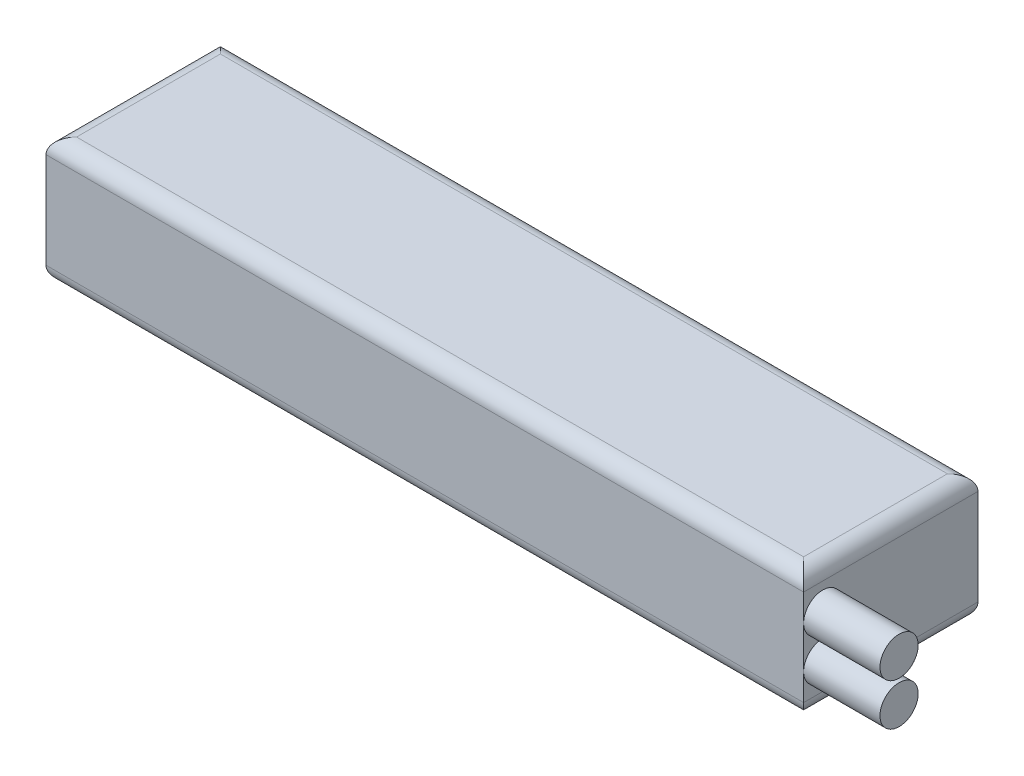
SolidWorks part; units mm, degrees
ref_plane "Front Plane" through (0, 0, 0) normal (0, 0, 1) x (1, 0, 0)
ref_plane "Top Plane" through (0, 0, 0) normal (0, 1, 0) x (1, 0, 0)
ref_plane "Right Plane" through (0, 0, 0) normal (1, 0, 0) x (0, 0, -1)
sketch "Sketch1" plane through (0, 0, 0) normal (0, 1, 0) x (1, 0, 0)
  line L1 (-2.7063, 0.7738) -> (123.2937, 0.7738)
  line L2 (-2.7063, 0.7738) -> (-2.7063, -28.2262)
  line L3 (-2.7063, -28.2262) -> (123.2937, -28.2262)
  line L4 (123.2937, 0.7738) -> (123.2937, -28.2262)
  dimension "D1" = 29
  dimension "D2" = 126
extrude "Boss-Extrude1" add sketch "Sketch1" along normal blind 21
sketch "Sketch2" plane through (123.2937, 0, 0) normal (1, 0, 0) x (0, 0, -1)
  line L0 (-28.2262, 10.5) -> (8.6283, 10.5) construction
  line L1 (-28.2262, 21) -> (-28.2262, 0) construction
  line L3 (-28.2262, 17.1675) -> (-21.8762, 17.1675) construction
  line L4 (-28.2262, 17.1675) -> (-28.2262, 3.8325) construction
  line L5 (-28.2262, 3.8325) -> (-21.8762, 3.8325) construction
  line L6 (-21.8762, 17.1675) -> (-21.8762, 3.8325) construction
  circle A0 centre (-25.0512, 13.9925) radius 3.175
  circle A1 centre (-25.0512, 7.0075) radius 3.175
  point P8 (-21.8762, 10.5)
  dimension "D1" = 6.35
  dimension "D2" = 13.335
extrude "Boss-Extrude2" add sketch "Sketch2" along normal blind 12.7
fillet "Fillet1" radius 2.54 8 edges at (60.2937, 0, 28.2262) (123.2937, 0, 13.7262) (60.2937, 0, -0.7738) (-2.7063, 0, 13.7262) (60.2937, 21, -0.7738) (123.2937, 21, 13.7262) (60.2937, 21, 28.2262) (-2.7063, 21, 13.7262)
